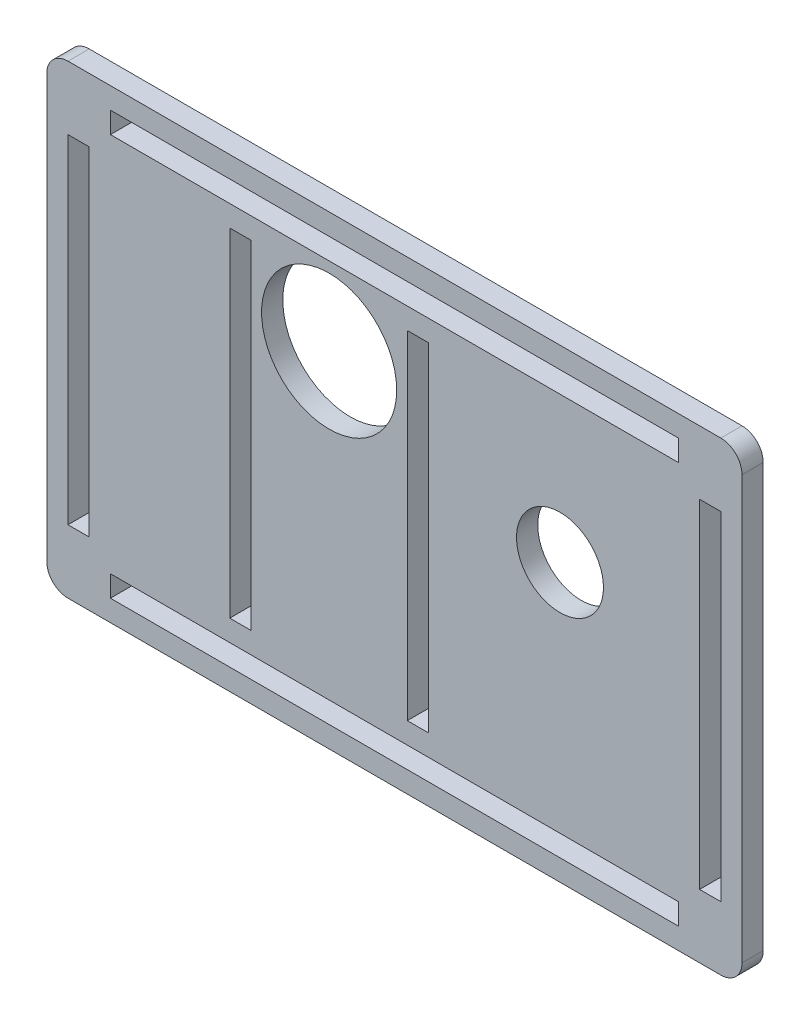
SolidWorks part; units mm, degrees
material "Acrylic (Medium-high impact)"
ref_plane "Front Plane" through (0, 0, 0) normal (0, 0, 1) x (1, 0, 0)
ref_plane "Top Plane" through (0, 0, 0) normal (0, 1, 0) x (1, 0, 0)
ref_plane "Right Plane" through (0, 0, 0) normal (1, 0, 0) x (0, 0, -1)
sketch "Sketch1" plane through (0, 0, 0) normal (0, 0, 1) x (1, 0, 0)
  line L1 (-127.5839, -254.6196) -> (67.8888, -254.6196)
  line L2 (-133.9339, -248.2696) -> (-133.9339, -121.7014)
  line L3 (-127.5839, -115.3514) -> (67.8888, -115.3514)
  line L4 (74.2388, -248.2696) -> (74.2388, -121.7014)
  line L9 (-79.1461, -134.4014) -> (-72.7961, -134.4014)
  line L10 (-72.7961, -134.4014) -> (-72.7961, -128.0514) construction
  line L11 (-72.7961, -134.4014) -> (-72.7961, -235.5696)
  line L12 (-72.7961, -235.5696) -> (-79.1461, -235.5696)
  line L13 (-79.1461, -235.5696) -> (-79.1461, -134.4014)
  line L14 (-121.2339, -134.4014) -> (-127.5839, -134.4014)
  line L15 (-127.5839, -134.4014) -> (-127.5839, -235.5696)
  line L16 (-127.5839, -235.5696) -> (-121.2339, -235.5696)
  line L17 (67.8888, -235.5696) -> (61.5388, -235.5696)
  line L18 (61.5388, -241.9196) -> (61.5388, -235.5696) construction
  line L19 (61.5388, -235.5696) -> (61.5388, -134.4014)
  line L20 (61.5388, -134.4014) -> (67.8888, -134.4014)
  line L23 (67.8888, -134.4014) -> (67.8888, -235.5696)
  line L24 (-19.6339, -134.4014) -> (-25.9839, -134.4014)
  line L25 (-25.9839, -134.4014) -> (-25.9839, -235.5696)
  line L26 (-25.9839, -235.5696) -> (-19.6339, -235.5696)
  line L28 (-19.6339, -235.5696) -> (-19.6339, -134.4014)
  line L29 (-121.2339, -235.5696) -> (-121.2339, -134.4014)
  line L30 (-114.8839, -128.0514) -> (55.1888, -128.0514) construction
  line L31 (55.1888, -128.0514) -> (55.1888, -121.7014) construction
  line L32 (55.1888, -121.7014) -> (-114.8839, -121.7014) construction
  line L33 (-114.8839, -121.7014) -> (-114.8839, -128.0514) construction
  line L34 (55.1888, -241.9196) -> (-114.8839, -241.9196) construction
  line L35 (-114.8839, -241.9196) -> (-114.8839, -248.2696) construction
  line L36 (-114.8839, -248.2696) -> (55.1888, -248.2696) construction
  line L37 (55.1888, -248.2696) -> (55.1888, -241.9196) construction
  line L38 (-114.8839, -128.0514) -> (55.1888, -128.0514)
  line L39 (55.1888, -128.0514) -> (55.1888, -121.7014)
  line L40 (55.1888, -121.7014) -> (-114.8839, -121.7014)
  line L41 (-114.8839, -121.7014) -> (-114.8839, -128.0514)
  line L42 (55.1888, -241.9196) -> (-114.8839, -241.9196)
  line L43 (-114.8839, -241.9196) -> (-114.8839, -248.2696)
  line L44 (-114.8839, -248.2696) -> (55.1888, -248.2696)
  line L45 (55.1888, -248.2696) -> (55.1888, -241.9196)
  arc A0 (67.8888, -115.3514) -> (74.2388, -121.7014) centre (67.8888, -121.7014) cw
  arc A1 (-133.9339, -121.7014) -> (-127.5839, -115.3514) centre (-127.5839, -121.7014) cw
  arc A2 (-127.5839, -254.6196) -> (-133.9339, -248.2696) centre (-127.5839, -248.2696) cw
  arc A3 (67.8888, -254.6196) -> (74.2388, -248.2696) centre (67.8888, -248.2696) ccw
  circle A10 centre (-49.39, -151.4575) radius 20.2311 construction
  circle A12 centre (19.7361, -171.6886) radius 13.0175 construction
  circle A13 centre (-49.39, -151.4575) radius 20.2311
  circle A14 centre (19.7361, -171.6886) radius 13.0175
  dimension "D3" = 6.35
  dimension "D1" = 6.35
extrude "Boss-Extrude1" add sketch "Sketch1" along normal blind 6.35
